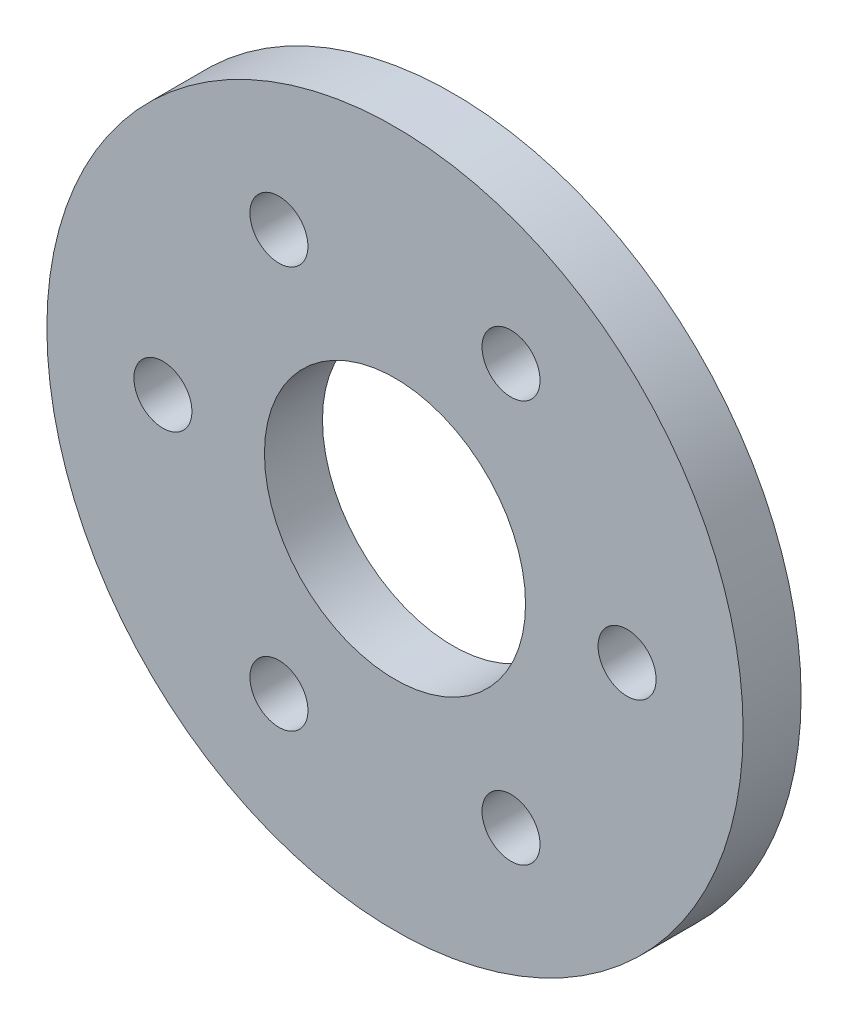
SolidWorks part; units mm, degrees
ref_plane "Front Plane" through (0, 0, 0) normal (0, 0, 1) x (1, 0, 0)
ref_plane "Top Plane" through (0, 0, 0) normal (0, 1, 0) x (1, 0, 0)
ref_plane "Right Plane" through (0, 0, 0) normal (1, 0, 0) x (0, 0, -1)
sketch "Sketch1" plane through (0, 0, 0) normal (0, 0, 1) x (1, 0, 0)
  line L0 (0, 0) -> (-25.4, 0) construction
  circle A0 centre (0, 0) radius 38.1
  circle A1 centre (0, 0) radius 25.4 construction
  point P18 (0, 0)
  dimension "D1" = 50.8
  dimension "D4" = 76.2
extrude "Boss-Extrude1" add sketch "Sketch1" along normal blind 6.35
sketch "Sketch2" plane through (0, 0, 6.35) normal (0, 0, 1) x (1, 0, 0)
  circle A1 centre (0, 0) radius 14.2875
  dimension "D1" = 28.575
sketch "Sketch4" plane through (0, 0, 0) normal (0, 0, -1) x (-1, 0, 0)
  circle A0 centre (0, 0) radius 25.4 construction
  circle A1 centre (-25.4, 0) radius 3.175
  circle A2 centre (0, 0) radius 25.4 construction
  circle A3 centre (-12.7, 21.997) radius 3.175
  circle A4 centre (0, 0) radius 25.4 construction
  circle A5 centre (12.7, 21.997) radius 3.175
  circle A6 centre (0, 0) radius 25.4 construction
  circle A7 centre (25.4, 0) radius 3.175
  circle A8 centre (0, 0) radius 25.4 construction
  circle A9 centre (12.7, -21.997) radius 3.175
  circle A10 centre (0, 0) radius 25.4 construction
  circle A11 centre (-12.7, -21.997) radius 3.175
  point P23 (0, 0)
  dimension "D1" = 50.8
  dimension "D2" = 6.35
  dimension "D3" = 6
extrude "Cut-Extrude2" cut sketch "Sketch4" against normal through all
extrude "Cut-Extrude3" cut sketch "Sketch2" against normal through all
